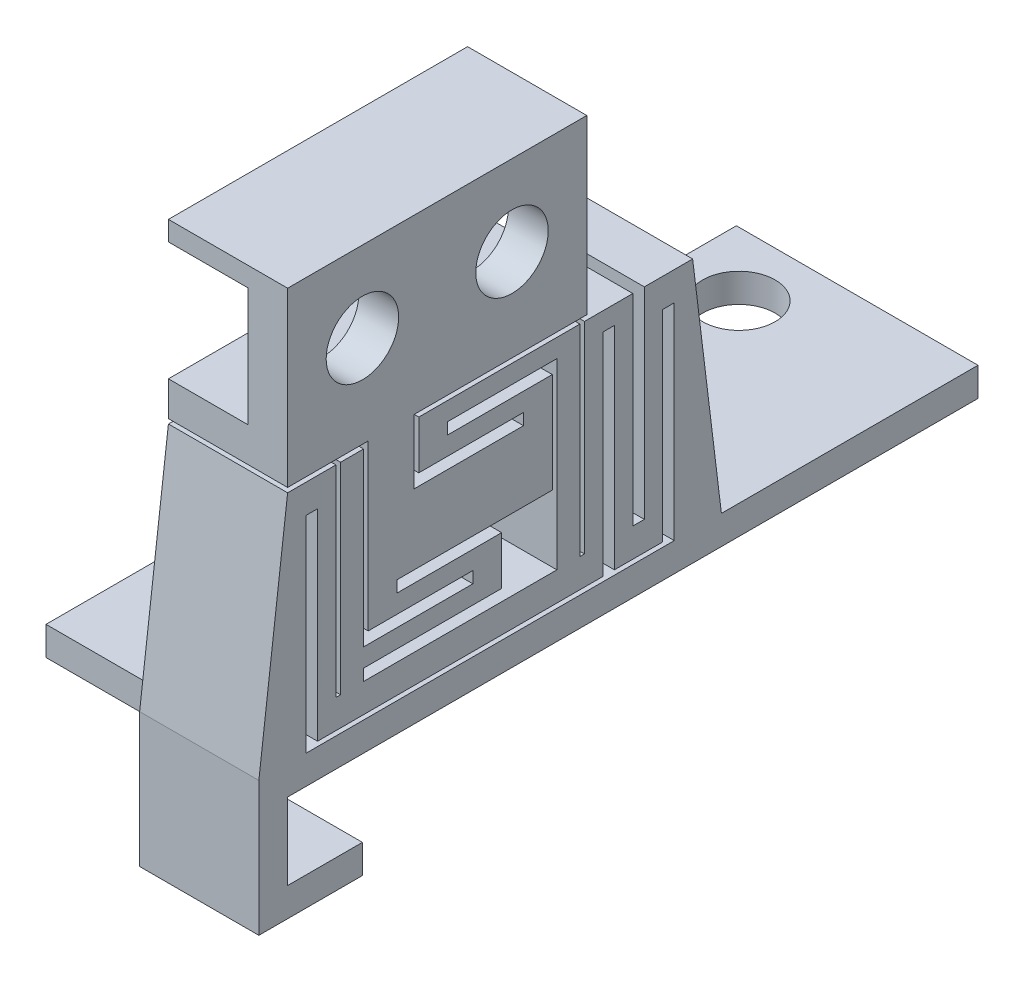
SolidWorks part; units mm, degrees
ref_plane "Front Plane" through (0, 0, 0) normal (0, 0, 1) x (1, 0, 0)
ref_plane "Top Plane" through (0, 0, 0) normal (0, 1, 0) x (1, 0, 0)
ref_plane "Right Plane" through (0, 0, 0) normal (1, 0, 0) x (0, 0, -1)
sketch "Sketch1" plane through (0, 0, 0) normal (1, 0, 0) x (0, 0, -1)
  line L0 (0, 0) -> (13, 0)
  line L1 (13, 0) -> (13, -7.5)
  line L2 (0, 0) -> (0, -7.5)
  line L3 (0, -7.5) -> (3.5, -7.5)
  line L4 (2.3, -7.7) -> (2.3, -16.45)
  line L7 (2.3, -16.45) -> (2.1, -16.45)
  line L8 (2.1, -16.45) -> (2.1, -7.7)
  line L9 (2.1, -7.7) -> (0, -7.7)
  line L10 (0, -7.7) -> (-1.25, -17.9)
  line L17 (5.7, -7.7) -> (12.7, -7.7)
  line L18 (13.7, -8.5) -> (13.7, -17.7)
  line L23 (13.7, -17.7) -> (1.3, -17.7)
  line L24 (1.3, -17.7) -> (1.3, -8.95)
  line L25 (1.3, -8.95) -> (0.8, -8.95)
  line L26 (0.8, -8.95) -> (0.8, -17.9)
  line L27 (0.8, -17.9) -> (16.8, -17.9)
  line L30 (13.7, -8.5) -> (14.2, -8.5)
  line L31 (14.2, -8.5) -> (14.2, -17.7)
  line L32 (15, -7.7) -> (15, -16.45)
  line L33 (15, -16.45) -> (15.5, -16.45)
  line L34 (15.5, -16.45) -> (15.5, -7.7)
  line L35 (15.5, -7.7) -> (17.6, -7.7)
  line L36 (14.2, -17.7) -> (16.3, -17.7)
  line L37 (16.3, -17.7) -> (16.3, -8.95)
  line L38 (16.3, -8.95) -> (16.8, -8.95)
  line L39 (16.8, -8.95) -> (16.8, -17.9)
  line L45 (0, -19.15) -> (18.85, -19.15)
  line L47 (18.85, -19.15) -> (18.85, -17.9)
  line L49 (17.6, -7.7) -> (18.85, -17.9)
  line L51 (-1.25, -17.9) -> (-1.25, -23.73)
  line L52 (-1.25, -23.73) -> (3.25, -23.73)
  line L53 (3.25, -23.73) -> (3.25, -22.48)
  line L54 (3.25, -22.48) -> (0, -22.48)
  line L55 (0, -22.48) -> (0, -19.15)
  line L57 (2.3, -7.7) -> (3.3, -7.7)
  line L58 (3.3, -7.7) -> (3.3, -15.15)
  line L59 (3.3, -16.45) -> (11.7, -16.45)
  line L60 (3.3, -16.45) -> (3.3, -15.95)
  line L61 (3.3, -15.95) -> (9.3, -15.95)
  line L62 (9.3, -15.95) -> (9.3, -13.85)
  line L63 (9.3, -13.85) -> (4.75, -13.85)
  line L64 (11.7, -16.45) -> (11.7, -8.5)
  line L65 (4.75, -13.35) -> (4.75, -13.85)
  line L66 (3.3, -15.15) -> (8.05, -15.15)
  line L67 (8.05, -15.15) -> (8.05, -14.65)
  line L68 (8.05, -14.65) -> (3.5, -14.65)
  line L69 (3.5, -14.65) -> (3.5, -7.5)
  line L70 (4.75, -13.35) -> (11.5, -13.35)
  line L71 (11.5, -13.35) -> (11.5, -9)
  line L72 (11.5, -9) -> (6.95, -9)
  line L73 (10.25, -10.3) -> (10.25, -9.8)
  line L74 (5.5, -7.5) -> (13, -7.5)
  line L76 (10.25, -9.8) -> (5.7, -9.8)
  line L77 (5.7, -9.8) -> (5.7, -7.7)
  line L78 (6.95, -9) -> (6.95, -8.5)
  line L79 (6.95, -8.5) -> (11.7, -8.5)
  line L80 (10.25, -10.3) -> (5.5, -10.3)
  line L81 (5.5, -10.3) -> (5.5, -7.5)
  line L82 (15, -7.7) -> (12.9, -7.7)
  line L83 (12.9, -7.7) -> (12.9, -16.45)
  line L84 (12.9, -16.45) -> (12.7, -16.45)
  line L85 (12.7, -16.45) -> (12.7, -7.7)
  point P49 (7.5, -17.7)
  point P68 (6.3, -15.95)
  dimension "D2" = 2.1
  dimension "D3" = 0.8
  dimension "D4" = 0.5
  dimension "D8" = 2.1
  dimension "D9" = 0.8
  dimension "D10" = 0.5
  dimension "D11" = 2.1
  dimension "D12" = 7.5
  dimension "D13" = 0.2
  dimension "D14" = 1.25
  dimension "D15" = 10
  dimension "D16" = 0.2
  dimension "D17" = 1.25
  dimension "D20" = 13
  dimension "D21" = 0.2
  dimension "D23" = 1.25
  dimension "D28" = 1.25
  dimension "D30" = 1.25
  dimension "D31" = 0.5
  dimension "D18" = 1.25
  dimension "D19" = 4.5
  dimension "D32" = 1.25
  dimension "D33" = 3.33
  dimension "D36" = 0.5
  dimension "D5" = 1
  dimension "D6" = 0.2
  dimension "D7" = 6
  dimension "D22" = 0.2
  dimension "D24" = 6
  dimension "D25" = 0.2
  dimension "D26" = 1.25
  dimension "D27" = 1.25
  dimension "D29" = 0.2
  dimension "D34" = 2.1
  dimension "D35" = 1
  dimension "D37" = 2
  dimension "D38" = 2.1
  dimension "D39" = 0.8
  dimension "D40" = 0.5
  dimension "D41" = 0.5
  dimension "D42" = 0.5
  dimension "D43" = 2.1
  dimension "D44" = 0.8
  dimension "D45" = 0.5
  dimension "D46" = 0.5
  dimension "D47" = 1.25
  dimension "D48" = 1.25
  dimension "D49" = 10
extrude "Boss-Extrude1" add sketch "Sketch1" along normal blind 5.18
sketch "Sketch2" plane through (0, 0, 0) normal (0, 0, 1) x (1, 0, 0)
  line L0 (5.18, 0) -> (5.18, -7.5) construction
  line L1 (5.18, -0.85) -> (1.73, -0.85)
  line L2 (5.18, -0.85) -> (5.18, -6)
  line L3 (5.18, -6) -> (1.73, -6)
  line L4 (1.73, -0.85) -> (1.73, -6)
  line L6 (5.18, -7.5) -> (0, -7.5) construction
  line L7 (5.18, 0) -> (0, 0) construction
  dimension "D1" = 3.45
  dimension "D2" = 1.5
  dimension "D3" = 0.85
extrude "Cut-Extrude1" cut sketch "Sketch2" against normal up to next
sketch "Sketch3" plane through (0, -19.15, 0) normal (0, -1, 0) x (1, 0, 0)
  line L0 (0, 1.25) -> (0, -3.25) construction
  line L1 (0, -30) -> (10.5, -30)
  line L2 (0, -30) -> (0, 0)
  line L3 (0, 0) -> (10.5, 0)
  line L4 (10.5, -30) -> (10.5, 0)
  line L6 (5.18, 0) -> (5.18, -18.85) construction
  line L7 (5.18, 1.25) -> (0, 1.25) construction
  circle A0 centre (7.62, -15.23) radius 1.575
  circle A1 centre (7.62, -27.23) radius 1.575
  dimension "D3" = 3.15
  dimension "D1" = 10.5
  dimension "D2" = 16.48
  dimension "D4" = 12
  dimension "D5" = 30
  dimension "D6" = 2.44
extrude "Boss-Extrude2" add sketch "Sketch3" against normal blind 1.25
sketch "Sketch7" plane through (0, 0, 0) normal (-1, 0, 0) x (0, 0, 1)
  line L0 (-13, 0) -> (0, 0) construction
  line L1 (0, 0) -> (0, -7.5) construction
  circle A0 centre (-3.25, -3.5) radius 1.575
  circle A1 centre (-9.75, -3.5) radius 1.575
  dimension "D1" = 3.15
  dimension "D2" = 3.5
  dimension "D3" = 3.25
  dimension "D4" = 6.5
extrude "Cut-Extrude3" cut sketch "Sketch7" against normal up to next
mirror "Mirror3" about plane through (0, 0, 0) normal (1, 0, 0) of bodies 105
delete or keep bodies "Body-Delete/Keep 1" type delete bodies bodies 105
equation "\"VerticalFlexureWidth\"= .8"
equation "\"VerticalFlexureGap\"= 0.5"
equation "\"VerticalDoubleFlexureWidth\"= 2 * \"VerticalFlexureWidth\" + \"VerticalFlexureGap\""
equation "\"D2@Sketch1\"=\"VerticalDoubleFlexureWidth\""
equation "\"D3@Sketch1\"=\"VerticalFlexureWidth\""
equation "\"D4@Sketch1\"=\"VerticalFlexureGap\""
equation "\"HorizontalFlexureLength\"= 6"
equation "\"FlexureJointWidth\"=1.25"
equation "\"D8@Sketch1\"=\"VerticalDoubleFlexureWidth\""
equation "\"D9@Sketch1\"=\"VerticalFlexureWidth\""
equation "\"D10@Sketch1\"=\"VerticalFlexureGap\""
equation "\"D11@Sketch1\"=\"VerticalDoubleFlexureWidth\""
equation "\"HeadHeight\"= 7.5"
equation "\"VerticalFlexureLength\"= 10"
equation "\"MinGap\"= 0.2"
equation "\"D12@Sketch1\"=\"HeadHeight\""
equation "\"D13@Sketch1\"=\"MinGap\""
equation "\"D14@Sketch1\"=\"FlexureJointWidth\""
equation "\"D15@Sketch1\"=\"VerticalFlexureLength\""
equation "\"D16@Sketch1\"=\"MinGap\""
equation "\"D17@Sketch1\"=\"FlexureJointWidth\""
equation "\"BaseplateHeight+Tolerance\"= 3.33"
equation "\"HeadWidth\"= 13"
equation "\"D20@Sketch1\"=\"HeadWidth\""
equation "\"D21@Sketch1\"=\"MinGap\""
equation "\"D28@Sketch1\"=\"FlexureJointWidth\""
equation "\"D30@Sketch1\"=\"FlexureJointWidth\""
equation "\"D31@Sketch1\"=\"VerticalFlexureGap\""
equation "\"D1@Boss-Extrude1\"= 5.18"
equation "\"D32@Sketch1\"=\"FlexureJointWidth\""
equation "\"D18@Sketch1\"=\"FlexureJointWidth\""
equation "\"HorizontalFlexureWidth\"= 0.8"
equation "\"HorizontalFlexureGap\"= 0.5"
equation "\"HorizontalDoubleFlexureWidth\"= 2 * \"HorizontalFlexureWidth\" + \"HorizontalFlexureGap\""
equation "\"D36@Sketch1\"=\"VerticalFlexureGap\""
equation "\"D1@Sketch8\"=\"VerticalFlexureGap\""
equation "\"D2@Sketch8\"=\"MinGap\""
equation "\"D3@Sketch8\"=\"MinGap\""
equation "\"Support\"= 1"
equation "\"D5@Sketch1\"=\"Support\""
equation "\"D6@Sketch1\"=\"MinGap\""
equation "\"D7@Sketch1\"=\"HorizontalFlexureLength\""
equation "\"D22@Sketch1\"=\"MinGap\""
equation "\"D24@Sketch1\"=\"HorizontalFlexureLength\""
equation "\"D25@Sketch1\"=\"MinGap\""
equation "\"D26@Sketch1\"=\"FlexureJointWidth\""
equation "\"D27@Sketch1\"=\"FlexureJointWidth\""
equation "\"D29@Sketch1\"=\"MinGap\""
equation "\"D34@Sketch1\"=\"VerticalDoubleFlexureWidth\""
equation "\"D38@Sketch1\"=\"HorizontalDoubleFlexureWidth\""
equation "\"D39@Sketch1\"=\"HorizontalFlexureWidth\""
equation "\"D40@Sketch1\"=\"HorizontalFlexureGap\""
equation "\"D41@Sketch1\"=\"HorizontalFlexureGap\""
equation "\"D42@Sketch1\"=\"HorizontalFlexureGap\""
equation "\"D43@Sketch1\"=\"HorizontalDoubleFlexureWidth\""
equation "\"D44@Sketch1\"=\"HorizontalFlexureWidth\""
equation "\"D45@Sketch1\"=\"HorizontalFlexureGap\""
equation "\"D46@Sketch1\"=\"HorizontalFlexureGap\""
equation "\"D47@Sketch1\"=\"FlexureJointWidth\""
equation "\"D48@Sketch1\"=\"FlexureJointWidth\""
equation "\"D49@Sketch1\"=\"VerticalFlexureLength\""
equation "\"D23@Sketch1\"=\"FlexureJointWidth\""
